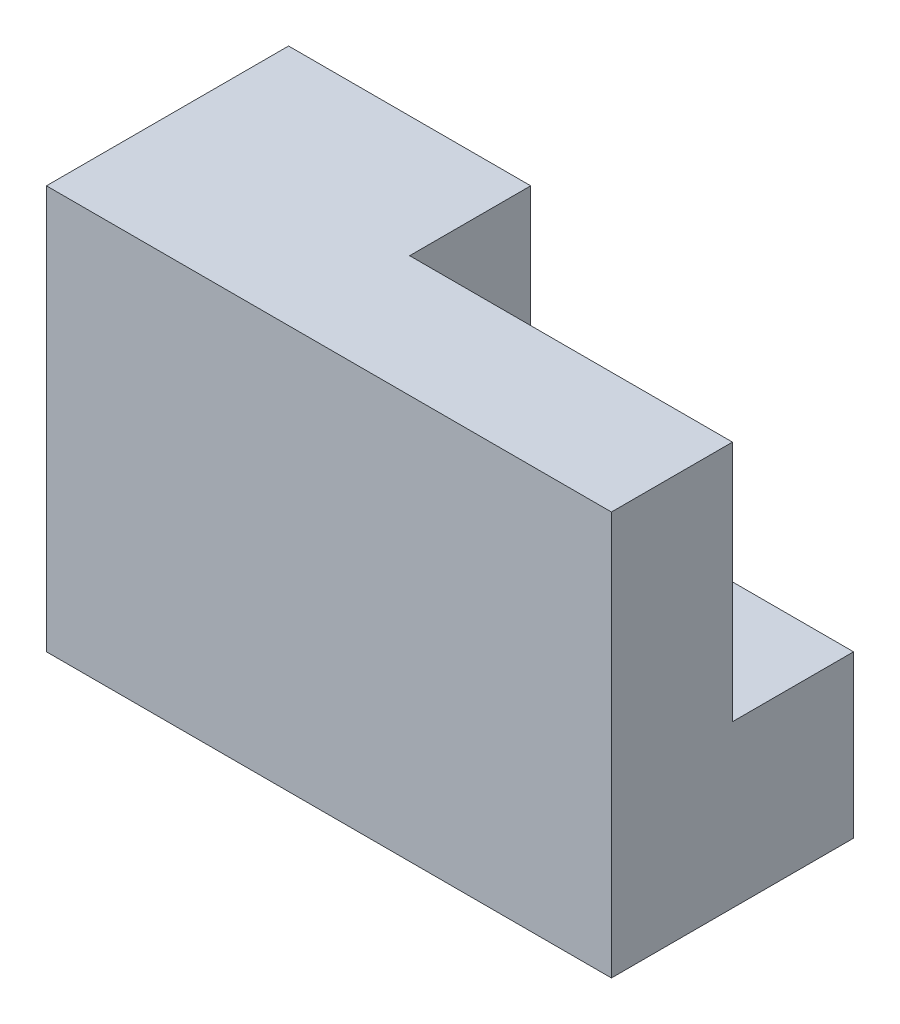
SolidWorks part; units mm, degrees
ref_plane "Front Plane" through (0, 0, 0) normal (0, 0, 1) x (1, 0, 0)
ref_plane "Top Plane" through (0, 0, 0) normal (0, 1, 0) x (1, 0, 0)
ref_plane "Right Plane" through (0, 0, 0) normal (1, 0, 0) x (0, 0, -1)
sketch "Sketch4" plane through (0, 0, 0) normal (0, 0, 1) x (1, 0, 0)
  line L1 (0, 0) -> (70, 0)
  line L2 (0, 0) -> (0, 20)
  line L3 (0, 20) -> (70, 20)
  line L4 (70, 0) -> (70, 20)
  dimension "D1" = 20
  dimension "D2" = 70
extrude "Boss-Extrude3" add sketch "Sketch4" along normal blind 30 and the other way blind 0.0001
sketch "Sketch6" plane through (0, 20, 0) normal (0, 1, 0) x (1, 0, 0)
  line L0 (70, 0.0001) -> (0, 0.0001) construction
  line L1 (0, -30) -> (30, -30)
  line L2 (0, -30) -> (0, 0.0001)
  line L3 (0, 0.0001) -> (30, 0.0001)
  line L4 (30, -30) -> (30, 0.0001)
  dimension "D1" = 30
extrude "Boss-Extrude4" add sketch "Sketch6" along normal blind 30
sketch "Sketch7" plane through (0, 20, 0) normal (0, 1, 0) x (1, 0, 0)
  line L0 (70, -30) -> (70, 0.0001) construction
  line L1 (30, -30) -> (70, -30)
  line L2 (30, -30) -> (30, -15)
  line L3 (30, -15) -> (70, -15)
  line L4 (70, -30) -> (70, -15)
extrude "Boss-Extrude5" add sketch "Sketch7" along normal blind 30
